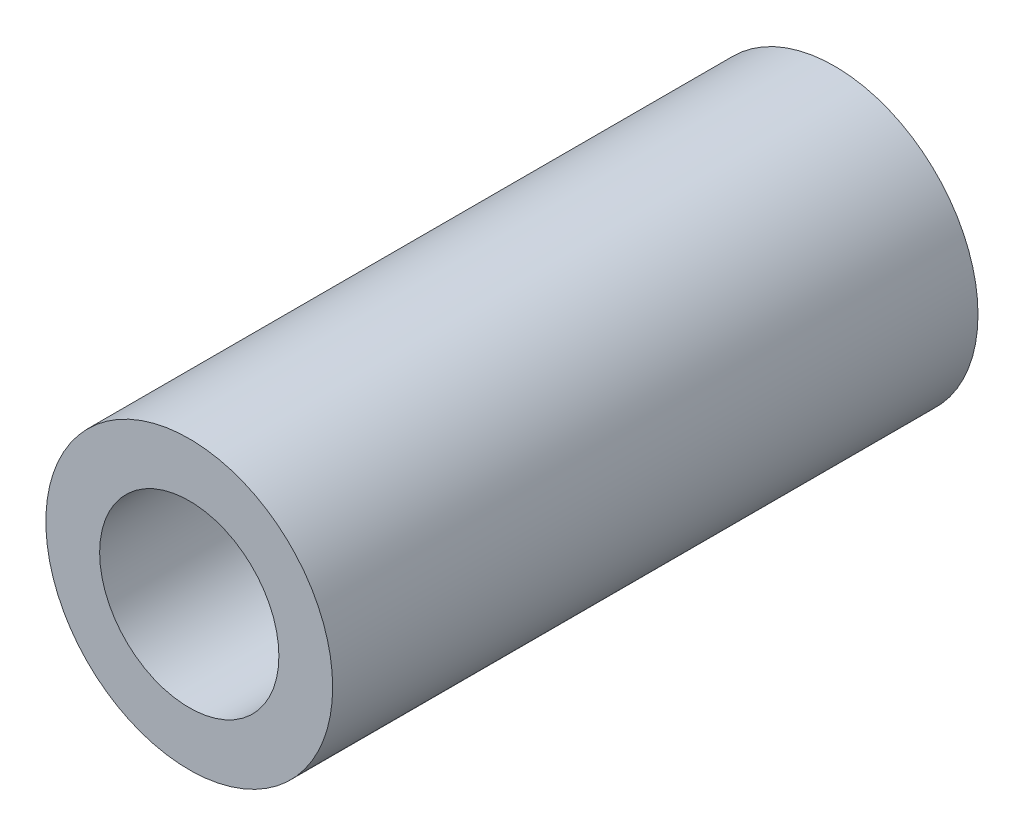
SolidWorks part; units mm, degrees
material "Chrome Stainless Steel"
ref_plane "Front Plane" through (0, 0, 0) normal (0, 0, 1) x (1, 0, 0)
ref_plane "Top Plane" through (0, 0, 0) normal (0, 1, 0) x (1, 0, 0)
ref_plane "Right Plane" through (0, 0, 0) normal (1, 0, 0) x (0, 0, -1)
sketch "Sketch1" plane through (0, 0, 0) normal (0, 0, 1) x (1, 0, 0)
  circle A0 centre (0, 0) radius 4
  circle A1 centre (0, 0) radius 2.5
  dimension "D1" = 8
  dimension "D2" = 1.5
extrude "Boss-Extrude1" add sketch "Sketch1" along normal blind 18
